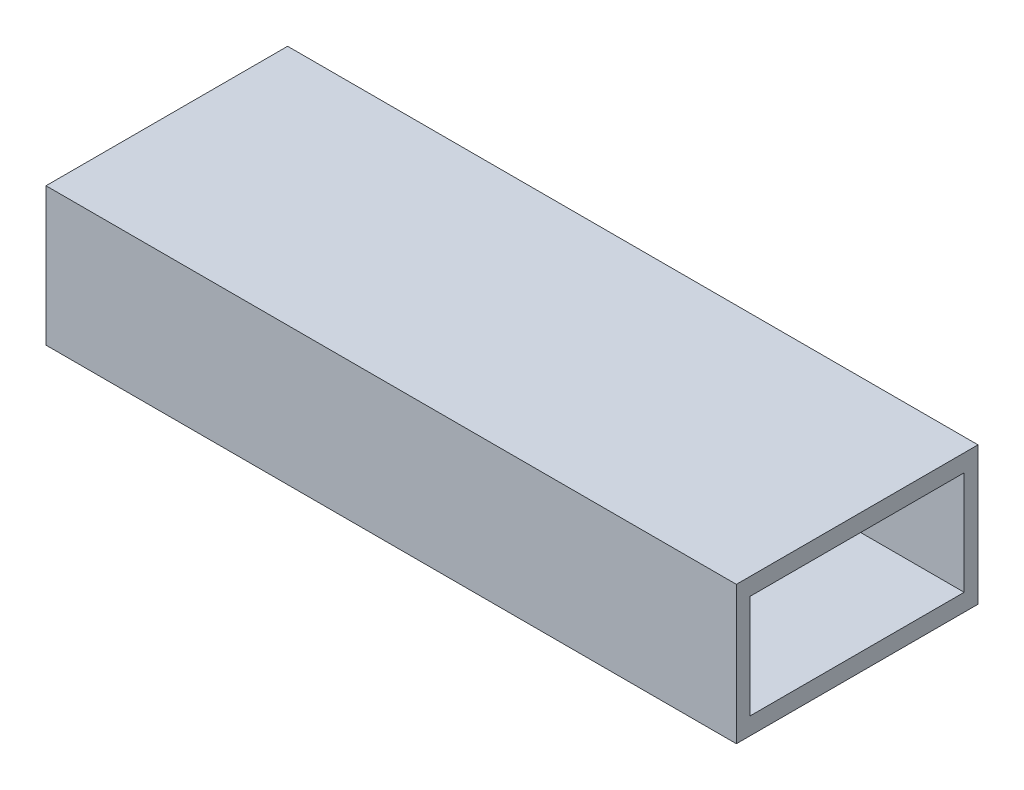
SolidWorks part; units mm, degrees
ref_plane "前视基准面" through (0, 0, 0) normal (0, 0, 1) x (1, 0, 0)
ref_plane "上视基准面" through (0, 0, 0) normal (0, 1, 0) x (1, 0, 0)
ref_plane "右视基准面" through (0, 0, 0) normal (1, 0, 0) x (0, 0, -1)
other "Configuration Table"
sketch "草图1" plane through (0, 0, 0) normal (1, 0, 0) x (0, 0, -1)
  line L1 (-15.5, 7.5) -> (15.5, 7.5)
  line L2 (-15.5, 7.5) -> (-15.5, -7.5)
  line L3 (-15.5, -7.5) -> (15.5, -7.5)
  line L4 (15.5, 7.5) -> (15.5, -7.5)
  line L5 (-15.5, 7.5) -> (15.5, -7.5) construction
  line L6 (-15.5, -7.5) -> (15.5, 7.5) construction
  line L7 (-17.5, 10) -> (17.5, 10)
  line L8 (-17.5, 10) -> (-17.5, -10)
  line L9 (-17.5, -10) -> (17.5, -10)
  line L10 (17.5, 10) -> (17.5, -10)
  line L11 (-17.5, 10) -> (17.5, -10) construction
  line L12 (-17.5, -10) -> (17.5, 10) construction
  point P0 (0, 0)
  point P6 (0, 0)
  dimension "D1" = 31
  dimension "D2" = 15
  dimension "D3" = 35
  dimension "D4" = 20
extrude "凸台-拉伸1" add sketch "草图1" along normal blind 100
